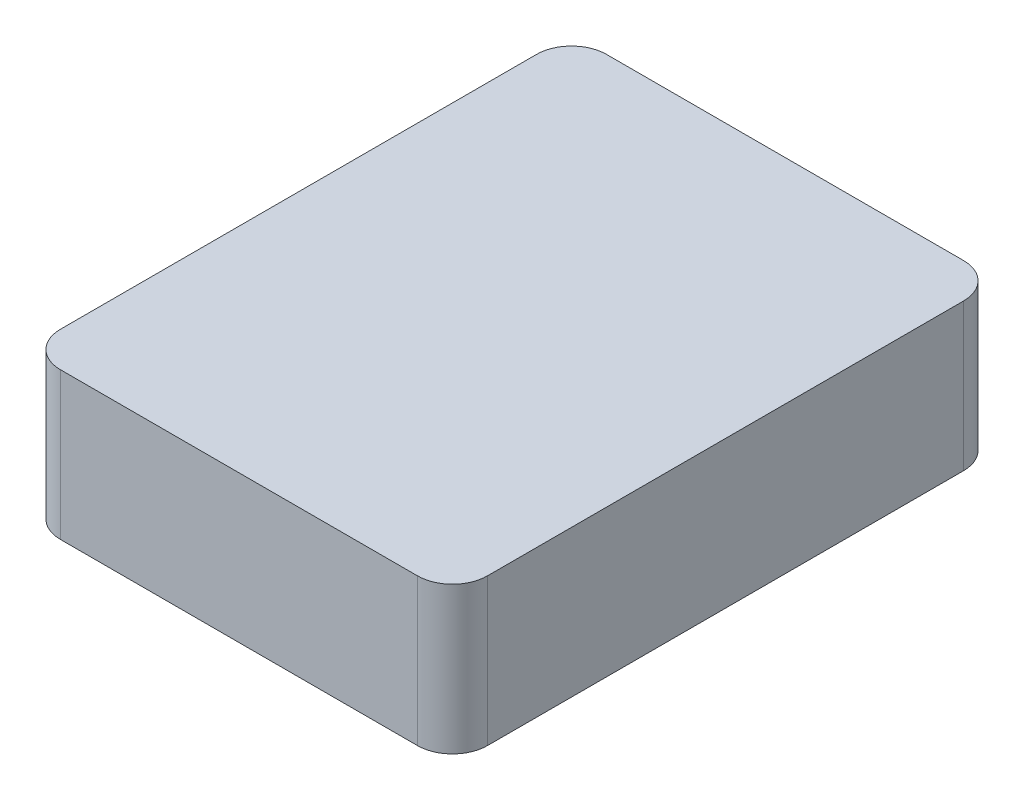
SolidWorks part; units mm, degrees
material "ABS"
ref_plane "Front Plane" through (0, 0, 0) normal (0, 0, 1) x (1, 0, 0)
ref_plane "Top Plane" through (0, 0, 0) normal (0, 1, 0) x (1, 0, 0)
ref_plane "Right Plane" through (0, 0, 0) normal (1, 0, 0) x (0, 0, -1)
sketch "Sketch1" plane through (0, 0, 0) normal (0, 1, 0) x (1, 0, 0)
  line L1 (0, 0) -> (61, 0)
  line L2 (0, 0) -> (0, 78)
  line L3 (0, 78) -> (61, 78)
  line L4 (61, 0) -> (61, 78)
  dimension "D1" = 78
  dimension "D2" = 61
extrude "Boss-Extrude1" add sketch "Sketch1" along normal blind 21
fillet "Fillet1" radius 5 4 edges at (0, 10.5, -78) (61, 10.5, -78) (61, 10.5, 0) (0, 10.5, 0)
